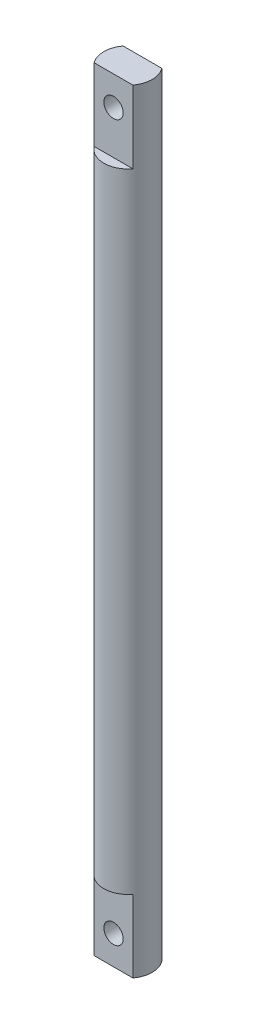
SolidWorks part; units mm, degrees
ref_plane "Front Plane" through (0, 0, 0) normal (0, 0, 1) x (1, 0, 0)
ref_plane "Top Plane" through (0, 0, 0) normal (0, 1, 0) x (1, 0, 0)
ref_plane "Right Plane" through (0, 0, 0) normal (1, 0, 0) x (0, 0, -1)
sketch "Sketch1" plane through (0, 0, 0) normal (0, 1, 0) x (1, 0, 0)
  circle A0 centre (0, 0) radius 5
  dimension "D1" = 10
extrude "Boss-Extrude1" add sketch "Sketch1" along normal mid plane 160
sketch "Sketch2" plane through (0, 80, 0) normal (0, 1, 0) x (1, 0, 0)
  line L0 (-4, -3) -> (4, -3)
  line L4 (-4, 3) -> (4, 3)
  circle A0 centre (0, 0) radius 5 construction
  arc A1 (4, 3) -> (-4, 3) centre (0, 0) ccw
  circle A2 centre (0, 0) radius 5
  arc A3 (-4, -3) -> (4, -3) centre (0, 0) ccw
  dimension "D1" = 6
  dimension "D2" = 3
  dimension "D3" = 0
extrude "Cut-Extrude1" cut sketch "Sketch2" against normal blind 15
mirror "Mirror2" about plane through (0, 0, 0) normal (0, 1, 0) of "Cut-Extrude1"
sketch "Sketch3" plane through (0, 0, 3) normal (0, 0, 1) x (1, 0, 0)
  line L0 (4, 80) -> (-4, 80) construction
  circle A0 centre (0, 74) radius 2
  point P5 (0, 80)
  dimension "D1" = 4
  dimension "D2" = 6
extrude "Cut-Extrude2" cut sketch "Sketch3" against normal through all
mirror "Mirror3" about plane through (0, 0, 0) normal (0, 1, 0) of "Cut-Extrude2"
